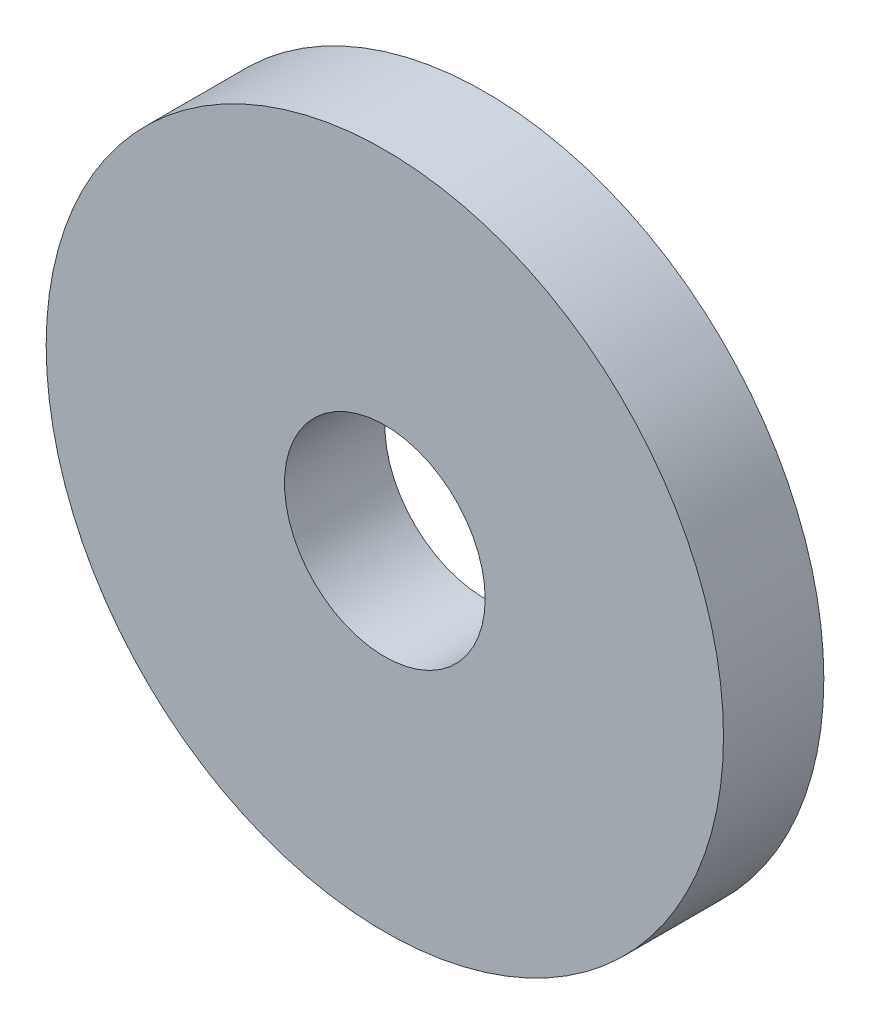
SolidWorks part; units mm, degrees
ref_plane "Front Plane" through (0, 0, 0) normal (0, 0, 1) x (1, 0, 0)
ref_plane "Top Plane" through (0, 0, 0) normal (0, 1, 0) x (1, 0, 0)
ref_plane "Right Plane" through (0, 0, 0) normal (1, 0, 0) x (0, 0, -1)
sketch "Sketch1" plane through (0, 0, 0) normal (0, 0, 1) x (1, 0, 0)
  circle A0 centre (0, 0) radius 4
  circle A1 centre (0, 0) radius 13.5
  dimension "D1" = 8
  dimension "D2" = 27
extrude "Boss-Extrude1" add sketch "Sketch1" along normal blind 4
